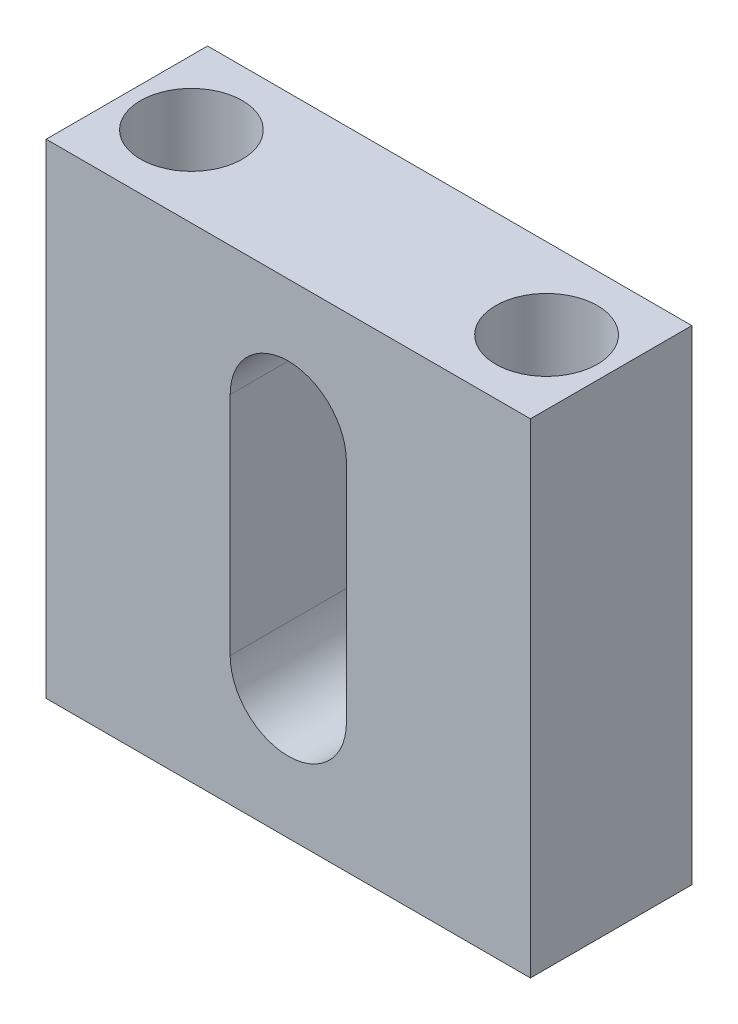
SolidWorks part; units mm, degrees
ref_plane "Front" through (0, 0, 0) normal (0, 0, 1) x (1, 0, 0)
ref_plane "Top" through (0, 0, 0) normal (0, 1, 0) x (1, 0, 0)
ref_plane "Right" through (0, 0, 0) normal (1, 0, 0) x (0, 0, -1)
sketch "Sketch1" plane through (0, 0, 0) normal (0, 0, 1) x (1, 0, 0)
  line L1 (0, 0) -> (19.05, 0)
  line L2 (0, 0) -> (0, 19.05)
  line L3 (0, 19.05) -> (19.05, 19.05)
  line L4 (19.05, 0) -> (19.05, 19.05)
  dimension "D1" = 19.05
  dimension "D2" = 19.05
extrude "Boss-Extrude1" add sketch "Sketch1" along normal blind 6.35
sketch "Sketch2" plane through (0, 0, 0) normal (0, -1, 0) x (1, 0, 0)
  line L0 (0, 6.35) -> (0, 0) construction
  line L1 (19.05, 6.35) -> (19.05, 0) construction
  circle A0 centre (2.54, 3.175) radius 2
  circle A1 centre (16.51, 3.175) radius 2
  point P7 (0, 3.175)
  dimension "D1" = 4
  dimension "D2" = 2.54
  dimension "D3" = 2.54
extrude "Cut-Extrude1" cut sketch "Sketch2" against normal through all
sketch "Sketch3" plane through (0, 0, 6.35) normal (0, 0, 1) x (1, 0, 0)
  line L1 (7.239, 13.97) -> (11.811, 13.97)
  line L2 (7.239, 13.97) -> (7.239, 5.08)
  line L3 (7.239, 5.08) -> (11.811, 5.08)
  line L4 (11.811, 13.97) -> (11.811, 5.08)
  line L5 (19.05, 19.05) -> (0, 19.05) construction
  line L6 (0, 0) -> (19.05, 0) construction
  circle A0 centre (9.525, 13.97) radius 2.286
  circle A1 centre (9.525, 5.08) radius 2.286
  point P8 (9.525, 19.05)
  dimension "D1" = 4.572
  dimension "D3" = 5.08
  dimension "D4" = 5.08
extrude "Cut-Extrude2" cut sketch "Sketch3" against normal through all contours L1 A0 | L1 A0 | A1 L4 A0 L2 | L3 A1 | L3 A1
